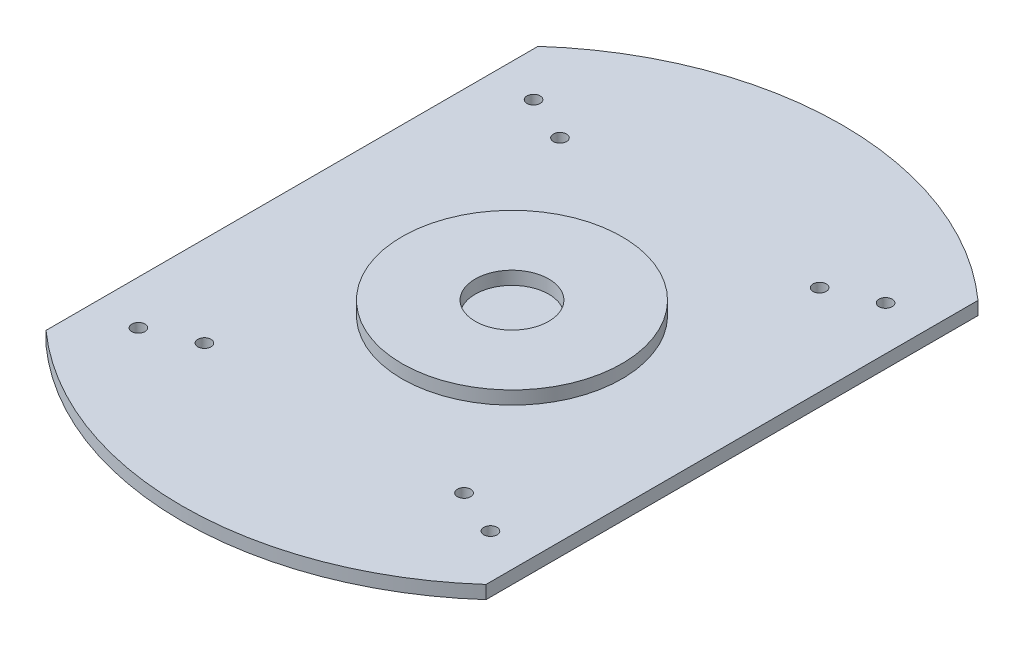
SolidWorks part; units mm, degrees
ref_plane "Front Plane" through (0, 0, 0) normal (0, 0, 1) x (1, 0, 0)
ref_plane "Top Plane" through (0, 0, 0) normal (0, 1, 0) x (1, 0, 0)
ref_plane "Right Plane" through (0, 0, 0) normal (1, 0, 0) x (0, 0, -1)
sketch "Sketch1" plane through (0, 0, 0) normal (0, 1, 0) x (1, 0, 0)
  line L0 (0, 0) -> (0, 9.8686) construction
  line L1 (38.5, 44.9) -> (40, 44.9)
  line L2 (50, 0) -> (50, 55.9017)
  line L3 (50, 0) -> (50, -55.9017)
  line L4 (-50, 0) -> (-50, 55.9017)
  line L5 (-50, 0) -> (-50, -55.9017)
  line L6 (0, 0) -> (11.2538, 0) construction
  line L7 (29.5, 38.9) -> (29.5, 40.4)
  arc A0 (-50, -55.9017) -> (50, -55.9017) centre (0, 0) ccw
  arc A1 (50, 55.9017) -> (-50, 55.9017) centre (0, 0) ccw
  circle A2 centre (40, 44.9) radius 1.5
  circle A3 centre (29.5, 40.4) radius 1.5
  circle A4 centre (-29.5, 40.4) radius 1.5
  circle A5 centre (-40, 44.9) radius 1.5
  circle A6 centre (29.5, -40.4) radius 1.5
  circle A7 centre (40, -44.9) radius 1.5
  circle A8 centre (-29.5, -40.4) radius 1.5
  circle A9 centre (-40, -44.9) radius 1.5
  dimension "D1" = 150
  dimension "D8" = 3
  dimension "D9" = 3
  dimension "D2" = 50
  dimension "D3" = 50
extrude "Boss-Extrude1" add sketch "Sketch1" along normal blind 3 contours L2 A1 L4 L5 A0 L3 A9 A8 A6 A4 A3 A2 A5 A7
sketch "Sketch2" plane through (0, 3, 0) normal (0, 1, 0) x (1, 0, 0)
  circle A0 centre (0, 0) radius 8.35
  circle A1 centre (0, 0) radius 25
  dimension "D1" = 16.7
  dimension "D2" = 50
extrude "Boss-Extrude2" add sketch "Sketch2" along normal blind 3
